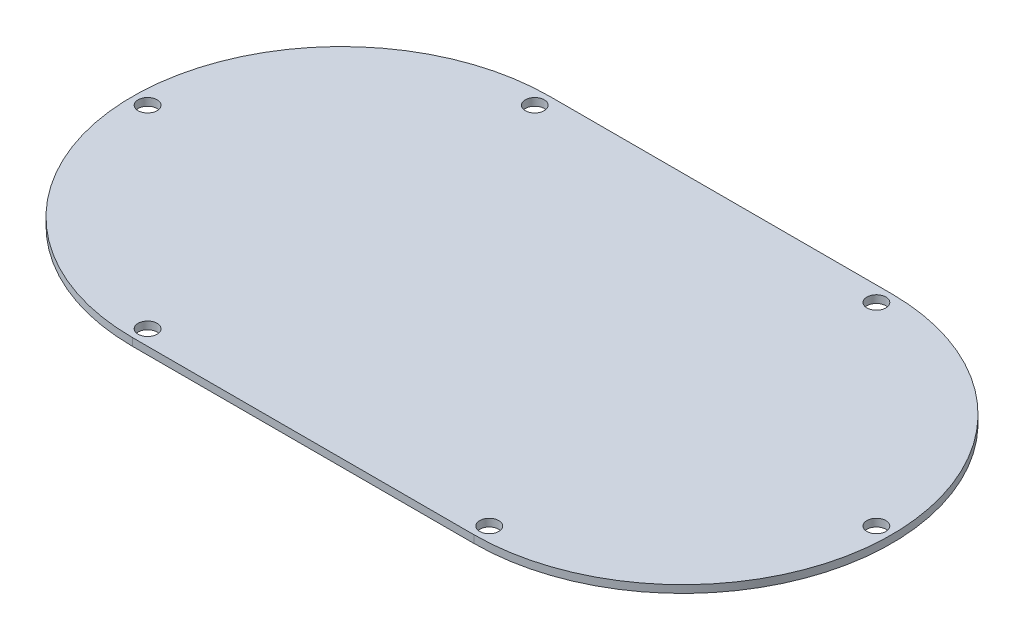
SolidWorks part; units mm, degrees
ref_plane "前视基准面" through (0, 0, 0) normal (0, 0, 1) x (1, 0, 0)
ref_plane "上视基准面" through (0, 0, 0) normal (0, 1, 0) x (1, 0, 0)
ref_plane "右视基准面" through (0, 0, 0) normal (1, 0, 0) x (0, 0, -1)
other "Configuration Table"
sketch "草图1" plane through (0, 0, 0) normal (0, 1, 0) x (1, 0, 0)
  line L0 (-45, 0) -> (45, 0) construction
  line L1 (-45, 55) -> (45, 55)
  line L2 (-45, -55) -> (45, -55)
  line L3 (0, 0) -> (0, 55) construction
  line L4 (45, 0) -> (96, 0) construction
  arc A0 (-45, 55) -> (-45, -55) centre (-45, 0) ccw
  arc A1 (45, -55) -> (45, 55) centre (45, 0) ccw
  circle A2 centre (-96, 0) radius 2.5
  circle A3 centre (-45, 51) radius 2.5
  circle A4 centre (45, 51) radius 2.5
  circle A5 centre (96, 0) radius 2.5
  circle A6 centre (45, -51) radius 2.5
  circle A7 centre (-45, -51) radius 2.5
  point P2 (0, 0)
  dimension "D1" = 200
  dimension "D2" = 55
  dimension "D3" = 5
  dimension "D5" = 5
  dimension "D4" = 192
  dimension "D6" = 102
  dimension "D7" = 90
extrude "凸台-拉伸1" add sketch "草图1" along normal blind 2
